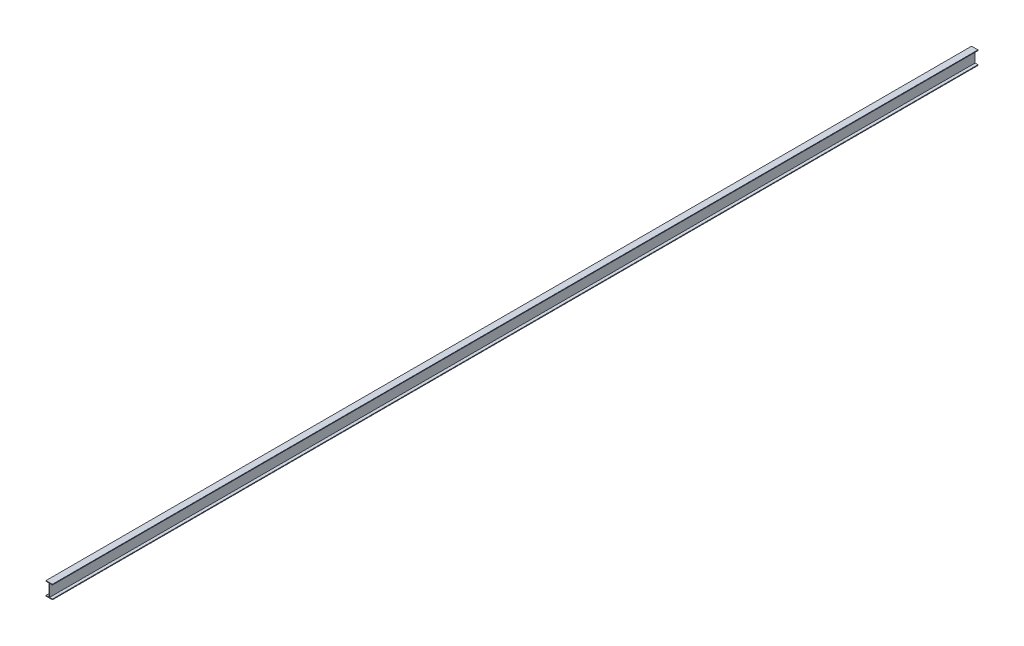
SolidWorks part; units mm, degrees
ref_plane "Front Plane" through (0, 0, 0) normal (0, 0, 1) x (1, 0, 0)
ref_plane "Top Plane" through (0, 0, 0) normal (0, 1, 0) x (1, 0, 0)
ref_plane "Right Plane" through (0, 0, 0) normal (1, 0, 0) x (0, 0, -1)
sketch "Sketch1" plane through (0, 0, 0) normal (0, 0, 1) x (1, 0, 0)
  line L0 (-31.75, 0) -> (31.75, 0)
  line L1 (0, 0) -> (0, -127)
  line L2 (-31.75, -127) -> (31.75, -127)
  point P7 (0, 0)
  point P8 (0, 0)
  point P9 (0, 0)
  point P10 (0, 0)
  dimension "D1" = 127
  dimension "D2" = 63.5
extrude "Extrude-Thin1" add sketch "Sketch1" along normal blind 9144 thin thin type mid plane wall 6.35
